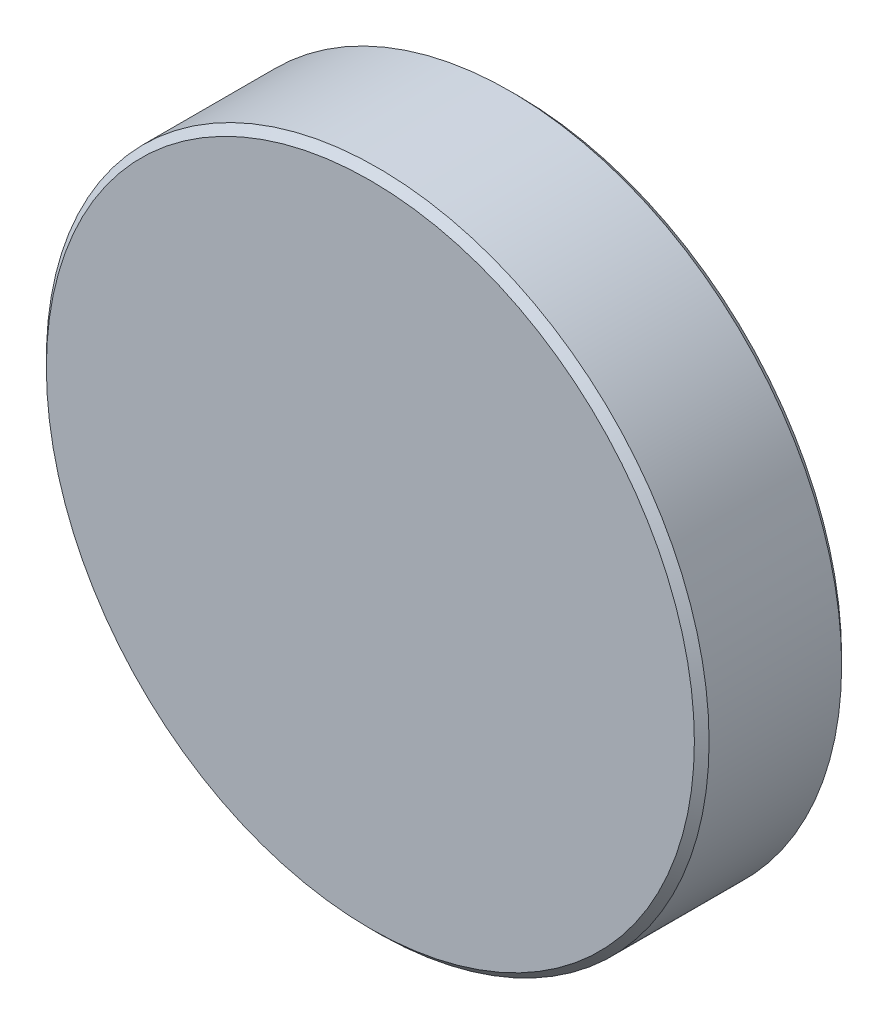
SolidWorks part; units mm, degrees
ref_plane "Front Plane" through (0, 0, 0) normal (0, 0, 1) x (1, 0, 0)
ref_plane "Top Plane" through (0, 0, 0) normal (0, 1, 0) x (1, 0, 0)
ref_plane "Right Plane" through (0, 0, 0) normal (1, 0, 0) x (0, 0, -1)
sketch "Sketch1" plane through (0, 0, 0) normal (0, 0, 1) x (1, 0, 0)
  circle A0 centre (0, 0) radius 4.5
  dimension "D1" = 9
extrude "Boss-Extrude1" add sketch "Sketch1" along normal blind 2
chamfer "Chamfer1" distance 0.1 angle 45 2 edges at (4.5, 0, 0) (4.5, 0, 2)
